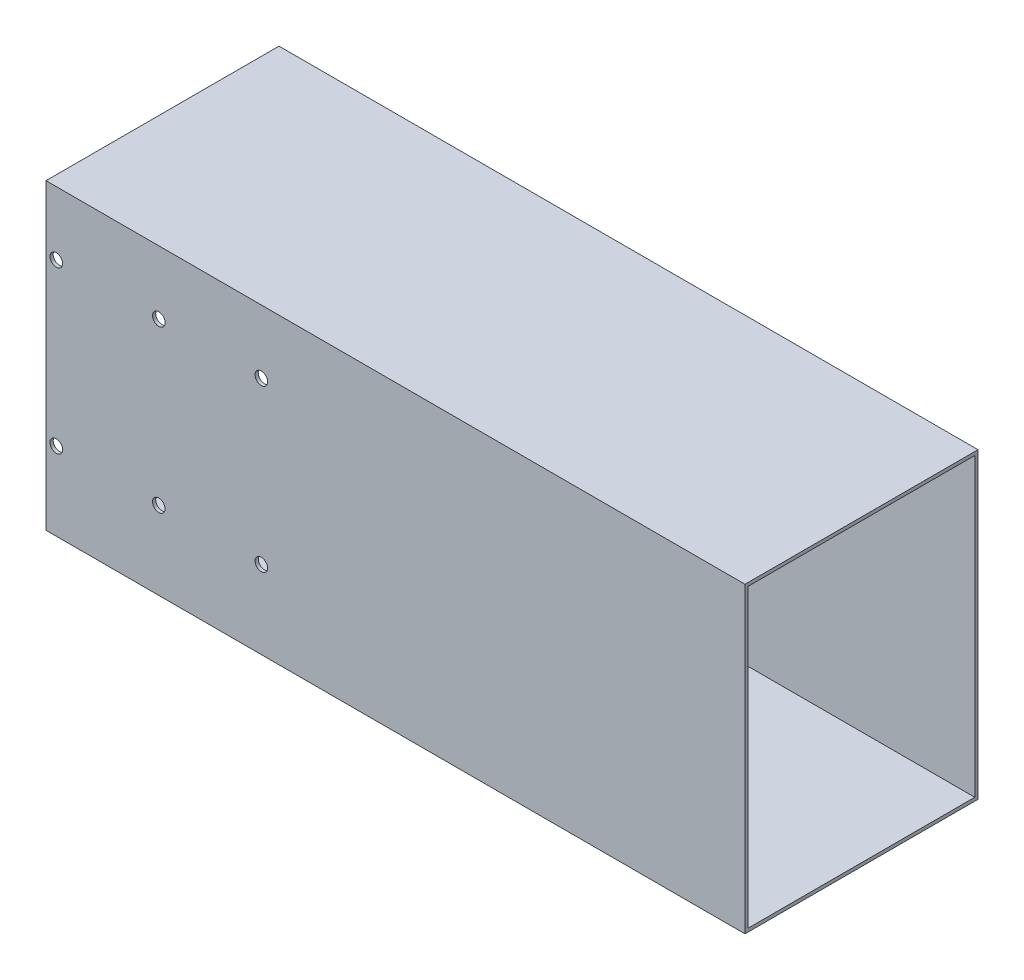
SolidWorks part; units mm, degrees
ref_plane "Plano frontal" through (0, 0, 0) normal (0, 0, 1) x (1, 0, 0)
ref_plane "Plano superior" through (0, 0, 0) normal (0, 1, 0) x (1, 0, 0)
ref_plane "Plano direito" through (0, 0, 0) normal (1, 0, 0) x (0, 0, -1)
sketch "Esboço1" plane through (0, 0, 0) normal (0, 0, 1) x (1, 0, 0)
  line L1 (136.0856, 44.5868) -> (-13.9144, 44.5868)
  line L2 (136.0856, 44.5868) -> (136.0856, -5.4132)
  line L3 (136.0856, -5.4132) -> (-13.9144, -5.4132)
  line L4 (-13.9144, 44.5868) -> (-13.9144, -5.4132)
  circle A0 centre (-11.7024, -3.6387) radius 1.35
  circle A3 centre (10.2976, -3.6387) radius 1.35
  circle A4 centre (32.2976, -3.6387) radius 1.35
  circle A5 centre (32.2976, 30.9613) radius 1.35
  circle A6 centre (10.2976, 30.9613) radius 1.35
  circle A7 centre (-11.7024, 30.9613) radius 1.35
  point P6 (0, 0)
  point P7 (0, 0)
  point P20 (0, 0)
  point P21 (0, 0)
  point P22 (0, 0)
  dimension "D1" = 2.7
  dimension "D2" = 2.7
  dimension "D3" = 2.7
  dimension "D4" = 22
  dimension "D5" = 50
  dimension "D6" = 150
  dimension "D7" = 44
  dimension "D8" = 34.6
  dimension "D9" = 34.6
  dimension "D10" = 34.6
extrude "Ressalto-extrusão1" add sketch "Esboço1" along normal blind 50
sketch "Esboço5" plane through (0, 0, 50) normal (0, 0, 1) x (1, 0, 0)
  line L1 (-13.9144, -5.4132) -> (136.0856, -5.4132)
  line L2 (-13.9144, -5.4132) -> (-13.9144, -20.3916)
  line L3 (-13.9144, -20.3916) -> (136.0856, -20.3916)
  line L4 (136.0856, -5.4132) -> (136.0856, -20.3916)
extrude "Ressalto-extrusão2" add sketch "Esboço5" against normal blind 50
sketch "Esboço6" plane through (-13.9144, 0, 0) normal (-1, 0, 0) x (0, 0, 1)
  line L1 (49.3171, 43.862) -> (0.6829, 43.862)
  line L2 (49.3171, 43.862) -> (49.3171, -19.6668)
  line L3 (49.3171, -19.6668) -> (0.6829, -19.6668)
  line L4 (0.6829, 43.862) -> (0.6829, -19.6668)
  line L5 (49.3171, 43.862) -> (0.6829, -19.6668) construction
  line L6 (49.3171, -19.6668) -> (0.6829, 43.862) construction
  point P0 (25, 12.0976)
extrude "Corte-extrusão6" cut sketch "Esboço6" against normal through all
